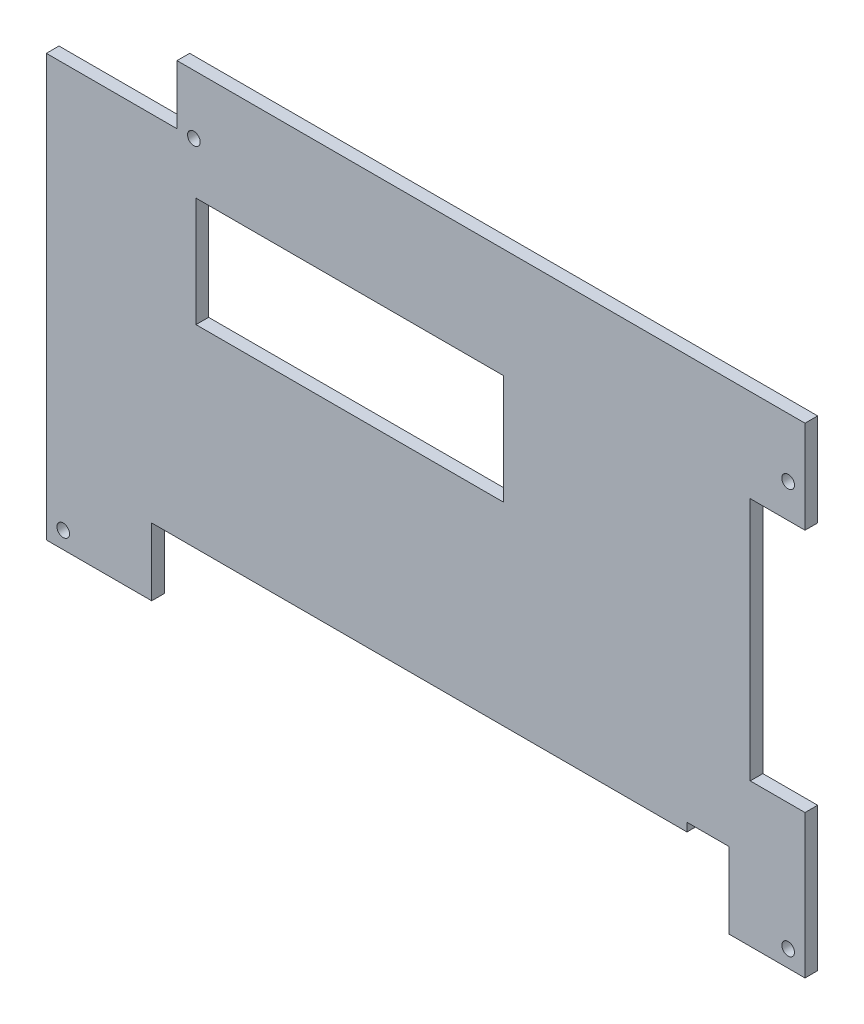
SolidWorks part; units mm, degrees
ref_plane "Front Plane" through (0, 0, 0) normal (0, 0, 1) x (1, 0, 0)
ref_plane "Top Plane" through (0, 0, 0) normal (0, 1, 0) x (1, 0, 0)
ref_plane "Right Plane" through (0, 0, 0) normal (1, 0, 0) x (0, 0, -1)
sketch "Sketch1" plane through (0, 0, 0) normal (0, 0, 1) x (1, 0, 0)
  line L0 (-40, -91) -> (-15, -91)
  line L1 (140, -91) -> (-40, -91) construction
  line L2 (-15, -91) -> (-15, -75)
  line L3 (-15, -75) -> (112, -75)
  line L4 (112, -75) -> (112, -73)
  line L5 (112, -73) -> (122, -73)
  line L6 (122, -73) -> (122, -91)
  line L7 (122, -91) -> (140, -91)
  line L8 (140, -91) -> (140, -57)
  line L9 (140, 39) -> (140, -91) construction
  line L10 (140, -57) -> (127, -57)
  line L11 (127, -57) -> (127, 1)
  line L12 (127, 1) -> (140, 1)
  line L13 (140, 1) -> (140, 23)
  line L14 (140, 23) -> (-9, 23)
  line L17 (-40, 9) -> (-40, -91)
  line L19 (-15, -75) -> (-4.5, -75) construction
  line L20 (-15, -75) -> (-15, -29) construction
  line L21 (-15, -29) -> (-4.5, -29) construction
  line L22 (-4.5, -75) -> (-4.5, -29) construction
  line L23 (-4.5, -29) -> (68.5, -29)
  line L24 (-4.5, -29) -> (-4.5, -3)
  line L25 (-4.5, -3) -> (68.5, -3)
  line L26 (68.5, -29) -> (68.5, -3)
  line L29 (-40, 9) -> (-9, 9)
  line L30 (-9, 23) -> (-9, 9)
  circle A0 centre (-5, 9) radius 1.5
  circle A1 centre (136, 9) radius 1.5
  circle A2 centre (136, -87) radius 1.5
  circle A3 centre (-36, -87) radius 1.5
  dimension "D1" = 3
  dimension "D2" = 3
  dimension "D3" = 3
  dimension "D4" = 3
  dimension "D5" = 25
  dimension "D6" = 16
  dimension "D7" = 127
  dimension "D8" = 2
  dimension "D9" = 10
  dimension "D10" = 18
  dimension "D11" = 18
  dimension "D12" = 34
  dimension "D13" = 13
  dimension "D14" = 58
  dimension "D15" = 22
  dimension "D17" = 46
  dimension "D18" = 10.5
  dimension "D19" = 26
  dimension "D20" = 73
extrude "Boss-Extrude1" add sketch "Sketch1" against normal blind 3
